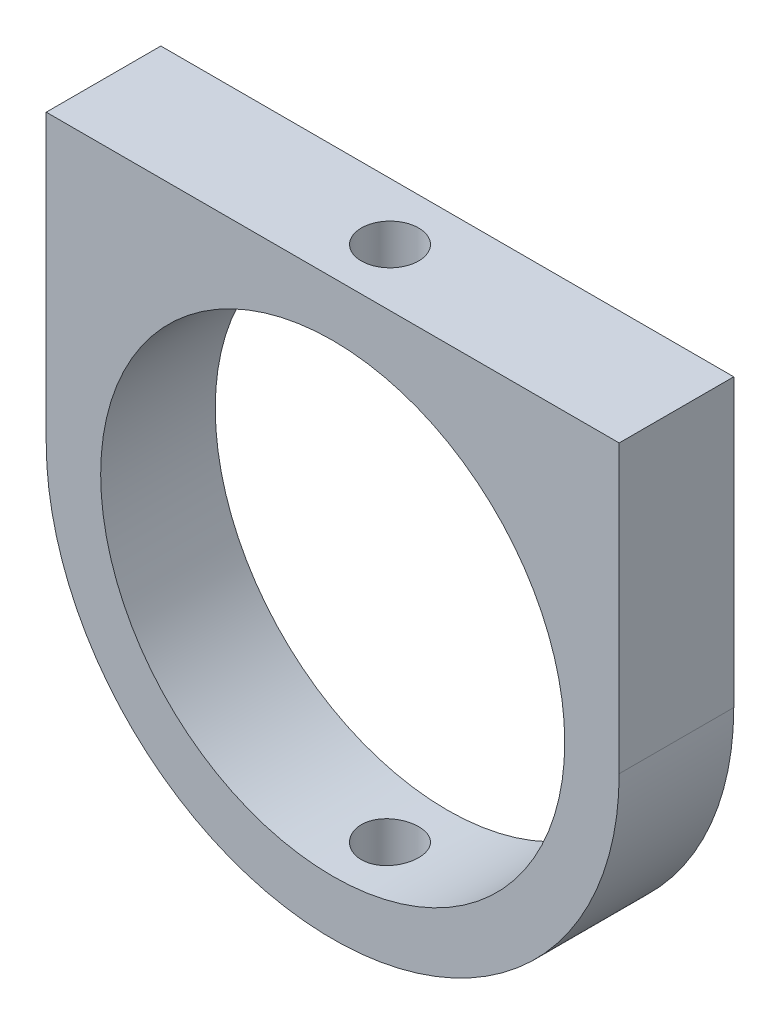
SolidWorks part; units mm, degrees
material "6063-T5"
ref_plane "Front Plane" through (0, 0, 0) normal (0, 0, 1) x (1, 0, 0)
ref_plane "Top Plane" through (0, 0, 0) normal (0, 1, 0) x (1, 0, 0)
ref_plane "Right Plane" through (0, 0, 0) normal (1, 0, 0) x (0, 0, -1)
sketch "Sketch1" plane through (0, 0, 0) normal (0, 0, 1) x (1, 0, 0)
  line L1 (-10, -10) -> (10, -10)
  line L2 (-10, -10) -> (-10, 10)
  line L3 (-10, 10) -> (10, 10)
  line L4 (10, -10) -> (10, 10)
  line L5 (-10, -10) -> (10, 10) construction
  line L6 (-10, 10) -> (10, -10) construction
  circle A0 centre (0, 0) radius 8.1
  arc A1 (-10, 0) -> (10, 0) centre (0, 0) ccw
  point P0 (0, 0)
extrude "Boss-Extrude1" add sketch "Sketch1" along normal blind 4 contours L2 A1 L4 L3 A0
sketch "Sketch3" plane through (0, 10, 0) normal (0, 1, 0) x (1, 0, 0)
  circle A0 centre (0, -2) radius 1
extrude "Cut-Extrude1" cut sketch "Sketch3" against normal blind 20
